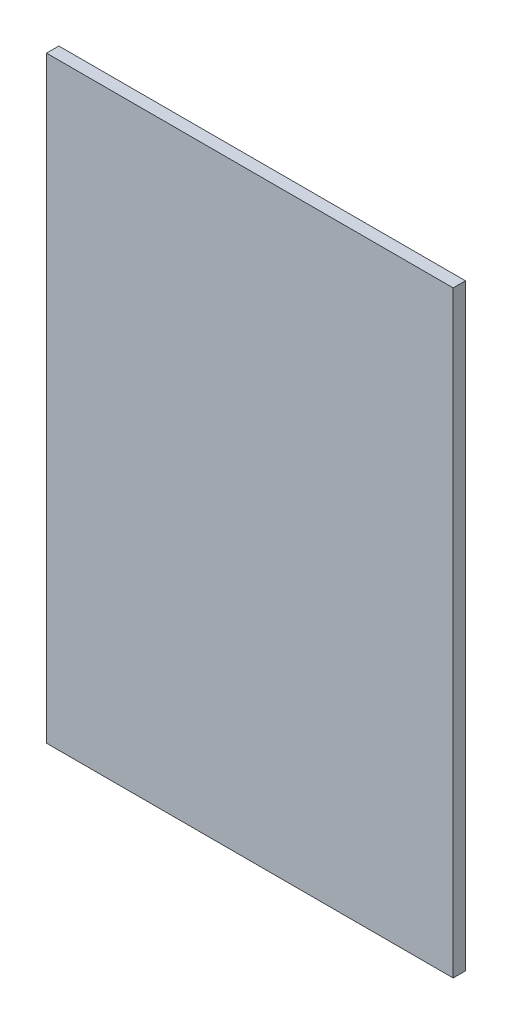
SolidWorks part; units mm, degrees
ref_plane "Plan de face" through (0, 0, 0) normal (0, 0, 1) x (1, 0, 0)
ref_plane "Plan de dessus" through (0, 0, 0) normal (0, 1, 0) x (1, 0, 0)
ref_plane "Plan de droite" through (0, 0, 0) normal (1, 0, 0) x (0, 0, -1)
sketch "Esquisse1" plane through (0, 0, 0) normal (0, 0, 1) x (1, 0, 0)
  line L1 (-57.2916, 66.989) -> (8.7084, 66.989)
  line L2 (-57.2916, 66.989) -> (-57.2916, -30.011)
  line L3 (-57.2916, -30.011) -> (8.7084, -30.011)
  line L4 (8.7084, 66.989) -> (8.7084, -30.011)
  dimension "D1" = 66
  dimension "D2" = 97
extrude "Boss.-Extru.1" add sketch "Esquisse1" along normal blind 2
sketch "Esquisse2" plane through (0, 0, 2) normal (0, 0, 1) x (1, 0, 0)
  line L0 (0.1277, 33.169) -> (0.1277, -27.831) construction
  line L1 (-3.1362, 33.169) -> (3.3977, 33.169)
  line L2 (-3.1362, 33.169) -> (-3.1362, -27.831)
  line L3 (-3.1362, -27.831) -> (3.3977, -27.831)
  line L4 (3.3977, 33.169) -> (3.3977, -27.831)
  line L5 (-47.6216, 66.989) -> (-47.6216, -30.011) construction
  line L6 (-45.447, -27.831) -> (-51.9809, -27.831)
  line L7 (-51.9809, 33.169) -> (-51.9809, -27.831)
  line L8 (-45.447, 33.169) -> (-51.9809, 33.169)
  line L10 (-0.9616, 66.989) -> (-0.9616, -30.011) construction
  line L11 (-24.2916, 66.989) -> (-24.2916, -30.011)
  line L12 (-24.2916, 66.989) -> (-24.2916, -30.011) construction
  line L13 (-45.447, 33.169) -> (-45.447, -27.831)
  line L15 (-57.2916, 33.169) -> (8.7084, 33.169) construction
  line L16 (-57.2916, -27.791) -> (8.7084, -27.791)
  line L17 (-57.2916, -27.791) -> (8.7084, -27.791) construction
  line L18 (-57.2916, 63.649) -> (8.7084, 63.649) construction
  circle A0 centre (-0.9616, -27.831) radius 1
  dimension "D1" = 6.5339
  dimension "D7" = 3.27
  dimension "D2" = 33
  dimension "D3" = 23.33
  dimension "D4" = 2.22
  dimension "D5" = 60.96
  dimension "D6" = 30.48
